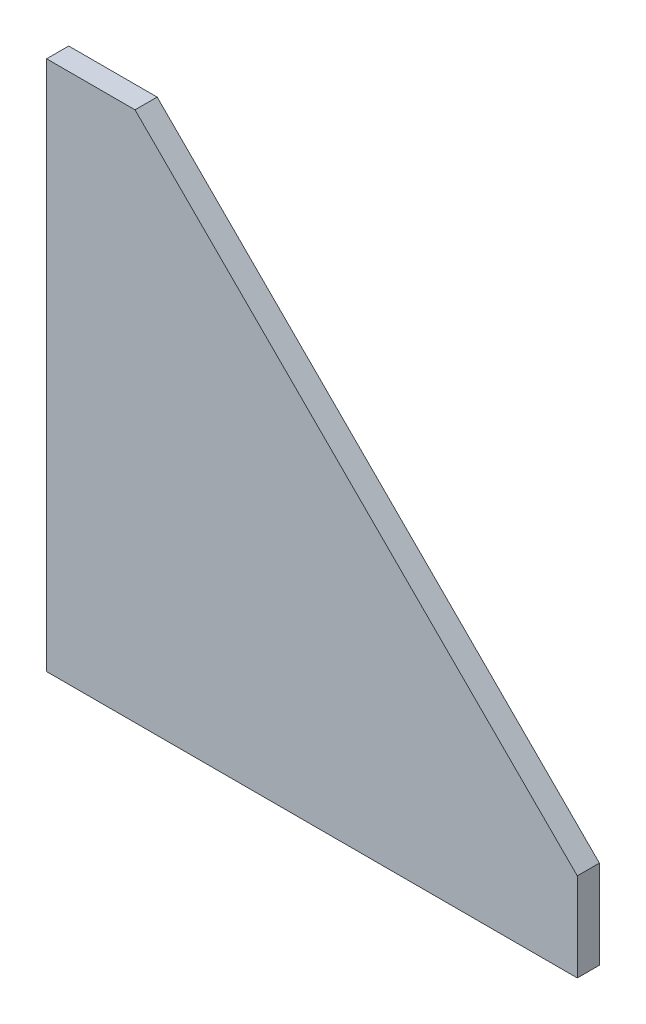
SolidWorks part; units mm, degrees
ref_plane "Front" through (0, 0, 0) normal (0, 0, 1) x (1, 0, 0)
ref_plane "Top" through (0, 0, 0) normal (0, 1, 0) x (1, 0, 0)
ref_plane "Right" through (0, 0, 0) normal (1, 0, 0) x (0, 0, -1)
sketch "Sketch1" plane through (0, 0, 0) normal (0, 0, 1) x (1, 0, 0)
  line L0 (0, 0) -> (0, 304.8)
  line L1 (0, 304.8) -> (50.8, 304.8)
  line L2 (50.8, 304.8) -> (304.8, 50.8)
  line L3 (304.8, 50.8) -> (304.8, 0)
  line L4 (304.8, 0) -> (0, 0)
other "AlignGroup1" parameters "D1"=50.9866, "D2"=50.8, "D3"=304.8
extrude "Boss-Extrude1" add sketch "Sketch1" along normal blind 12.7
